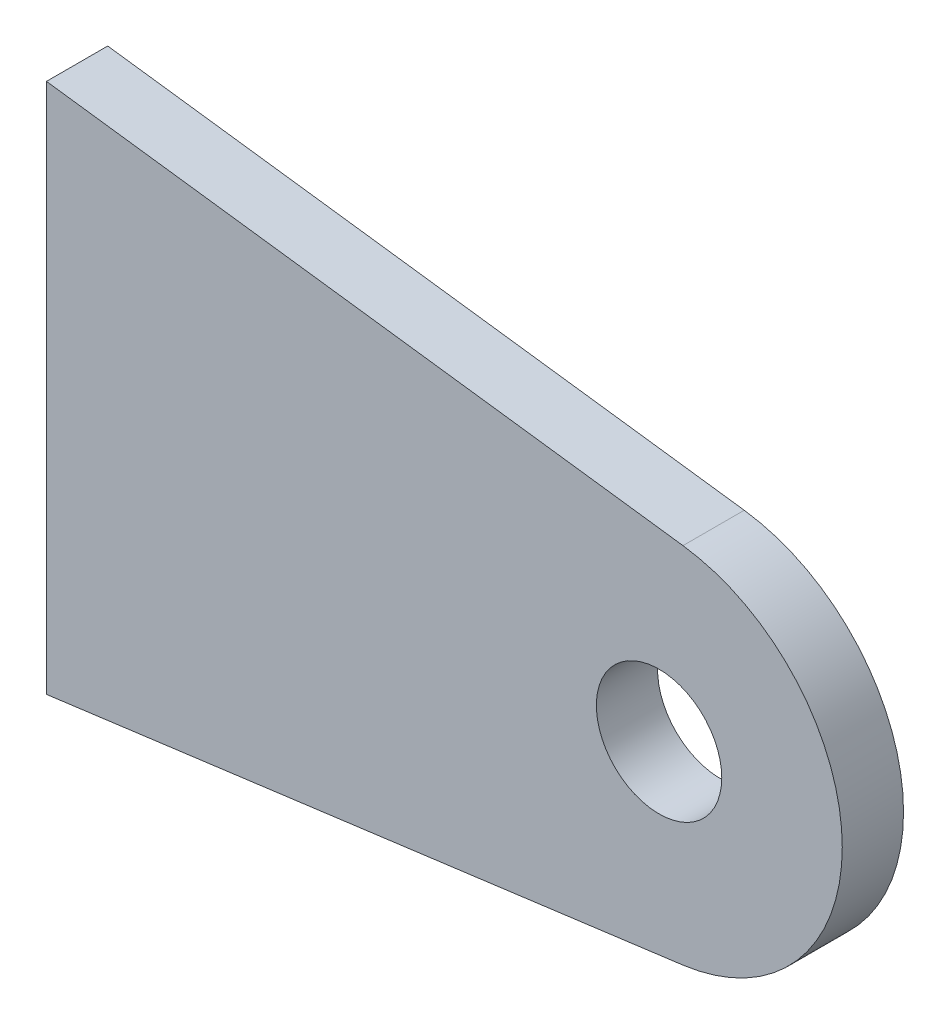
SolidWorks part; units mm, degrees
material "AISI 4130 Steel, annealed at 865C"
ref_plane "X-Y Datum" through (0, 0, 0) normal (0, 0, 1) x (1, 0, 0)
ref_plane "X-Z Datum" through (0, 0, 0) normal (0, 1, 0) x (1, 0, 0)
ref_plane "Y-Z Datum" through (0, 0, 0) normal (1, 0, 0) x (0, 0, -1)
sketch "Sketch1" plane through (-1053.7408, 0, 0) normal (0, 0, 1) x (1, 0, 0)
  line L0 (1054.9803, -9.4147) -> (1021.9908, -13.7578)
  line L1 (1054.9803, 9.4147) -> (1021.9908, 13.7578)
  line L2 (1021.9908, -13.7578) -> (1021.9908, 13.7578)
  circle A0 centre (1053.7408, 0) radius 3.25
  circle A1 centre (1053.7408, 0) radius 9.4959
  circle A4 centre (1053.7408, 0) radius 11.43 construction
  dimension "D3" = 18.9919
  dimension "D4" = 6.5
  dimension "D5" = 22.86
  dimension "D1" = 15
  dimension "D2" = 31.75
extrude "Boss-Extrude1" add sketch "Sketch1" along normal blind 3.175
